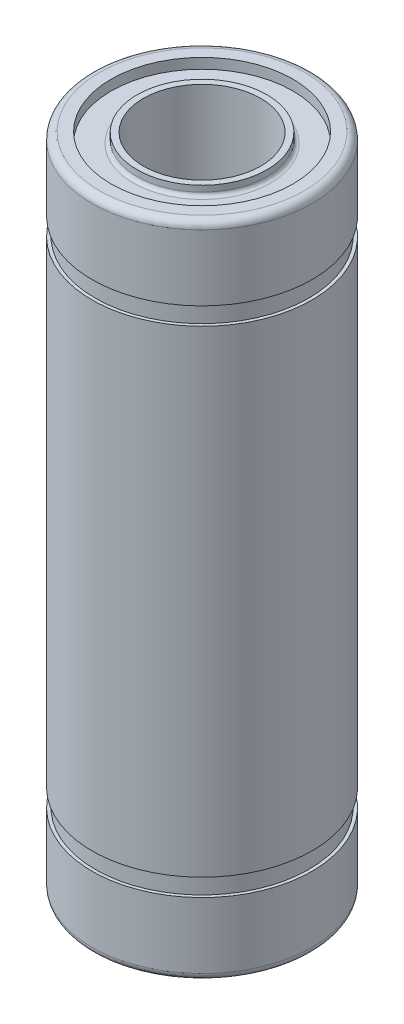
SolidWorks part; units mm, degrees
ref_plane "Front Plane" through (0, 0, 0) normal (0, 0, 1) x (1, 0, 0)
ref_plane "Top Plane" through (0, 0, 0) normal (0, 1, 0) x (1, 0, 0)
ref_plane "Right Plane" through (0, 0, 0) normal (1, 0, 0) x (0, 0, -1)
sketch "Sketch1" plane through (0, 0, 0) normal (0, 0, 1) x (1, 0, 0)
  line L0 (4.425, 22.4004) -> (4, 22.4004)
  line L1 (4, 22.4004) -> (4, -22.4004)
  line L2 (4, -22.4004) -> (4.425, -22.4004)
  line L3 (4.425, -22.4004) -> (4.425, -21.994)
  line L4 (4.679, -21.74) -> (6.19, -21.74)
  line L5 (6.19, -21.74) -> (6.19, -22.44)
  line L6 (6.19, -22.44) -> (6.982, -22.44)
  line L7 (7.49, -21.932) -> (7.49, -17.45)
  line L8 (7.49, -17.45) -> (7.275, -17.45)
  line L9 (7.275, -17.45) -> (7.275, -16.25)
  line L10 (7.275, -16.25) -> (7.49, -16.25)
  line L11 (7.49, -16.25) -> (7.49, 16.25)
  line L12 (7.49, 16.25) -> (7.275, 16.25)
  line L13 (7.275, 16.25) -> (7.275, 17.45)
  line L14 (7.275, 17.45) -> (7.49, 17.45)
  line L15 (7.49, 17.45) -> (7.49, 21.932)
  line L16 (6.982, 22.44) -> (6.19, 22.44)
  line L17 (6.19, 22.44) -> (6.19, 21.74)
  line L18 (6.19, 21.74) -> (4.679, 21.74)
  line L19 (4.425, 21.994) -> (4.425, 22.4004)
  line L20 (0, 22.4413) -> (0, -22.4413) construction
  arc A0 (4.425, -21.994) -> (4.679, -21.74) centre (4.679, -21.994) cw
  arc A1 (6.982, -22.44) -> (7.49, -21.932) centre (6.982, -21.932) ccw
  arc A2 (7.49, 21.932) -> (6.982, 22.44) centre (6.982, 21.932) ccw
  arc A3 (4.679, 21.74) -> (4.425, 21.994) centre (4.679, 21.994) cw
revolve "Revolve1" add sketch "Sketch1" angle 360 about L20
